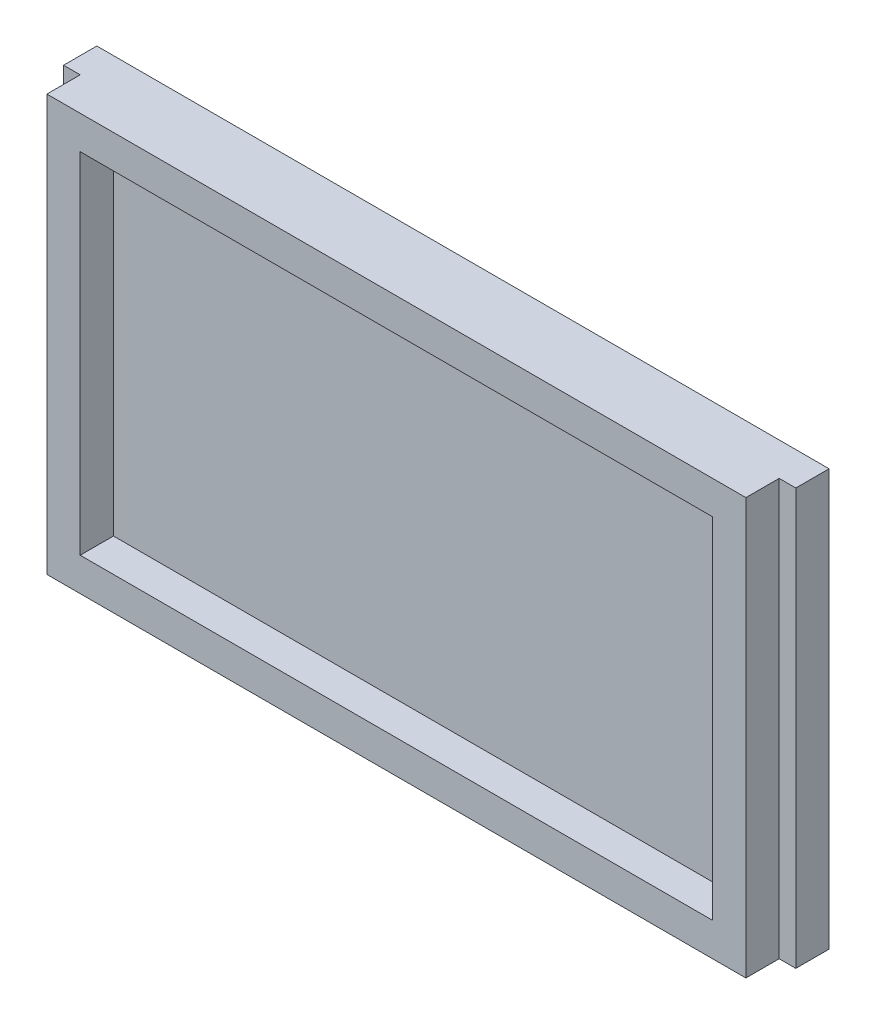
SolidWorks part; units mm, degrees
ref_plane "Ön Düzlem" through (0, 0, 0) normal (0, 0, 1) x (1, 0, 0)
ref_plane "Üst Düzlem" through (0, 0, 0) normal (0, 1, 0) x (1, 0, 0)
ref_plane "Sağ Düzlem" through (0, 0, 0) normal (1, 0, 0) x (0, 0, -1)
sketch "Çizim1" plane through (0, 0, 0) normal (0, 0, 1) x (1, 0, 0)
  line L1 (-22, 12.5) -> (22, 12.5)
  line L2 (-22, 12.5) -> (-22, -12.5)
  line L3 (-22, -12.5) -> (22, -12.5)
  line L4 (22, 12.5) -> (22, -12.5)
  line L5 (-22, 12.5) -> (22, -12.5) construction
  line L6 (-22, -12.5) -> (22, 12.5) construction
  point P0 (0, 0)
  dimension "D1" = 44
  dimension "D2" = 25
extrude "Yükseklik-Ekstrüzyon1" add sketch "Çizim1" along normal blind 2
sketch "Çizim3" plane through (0, 0, 2) normal (0, 0, 1) x (1, 0, 0)
  line L1 (-21, 12.5) -> (21, 12.5)
  line L2 (-21, 12.5) -> (-21, -12.5)
  line L3 (-21, -12.5) -> (21, -12.5)
  line L4 (21, 12.5) -> (21, -12.5)
  line L5 (-21, 12.5) -> (21, -12.5) construction
  line L6 (-21, -12.5) -> (21, 12.5) construction
  point P0 (0, 0)
  dimension "D1" = 42
  dimension "D2" = 25
extrude "Yükseklik-Ekstrüzyon2" add sketch "Çizim3" along normal blind 2
sketch "Çizim5" plane through (0, 0, 4) normal (0, 0, 1) x (1, 0, 0)
  line L1 (-19, 10.5) -> (19, 10.5)
  line L2 (-19, 10.5) -> (-19, -10.5)
  line L3 (-19, -10.5) -> (19, -10.5)
  line L4 (19, 10.5) -> (19, -10.5)
  line L5 (-19, 10.5) -> (19, -10.5) construction
  line L6 (-19, -10.5) -> (19, 10.5) construction
  point P0 (0, 0)
  dimension "D1" = 38
  dimension "D2" = 21
extrude "Kes-Ekstrüzyon1" cut sketch "Çizim5" against normal blind 2
